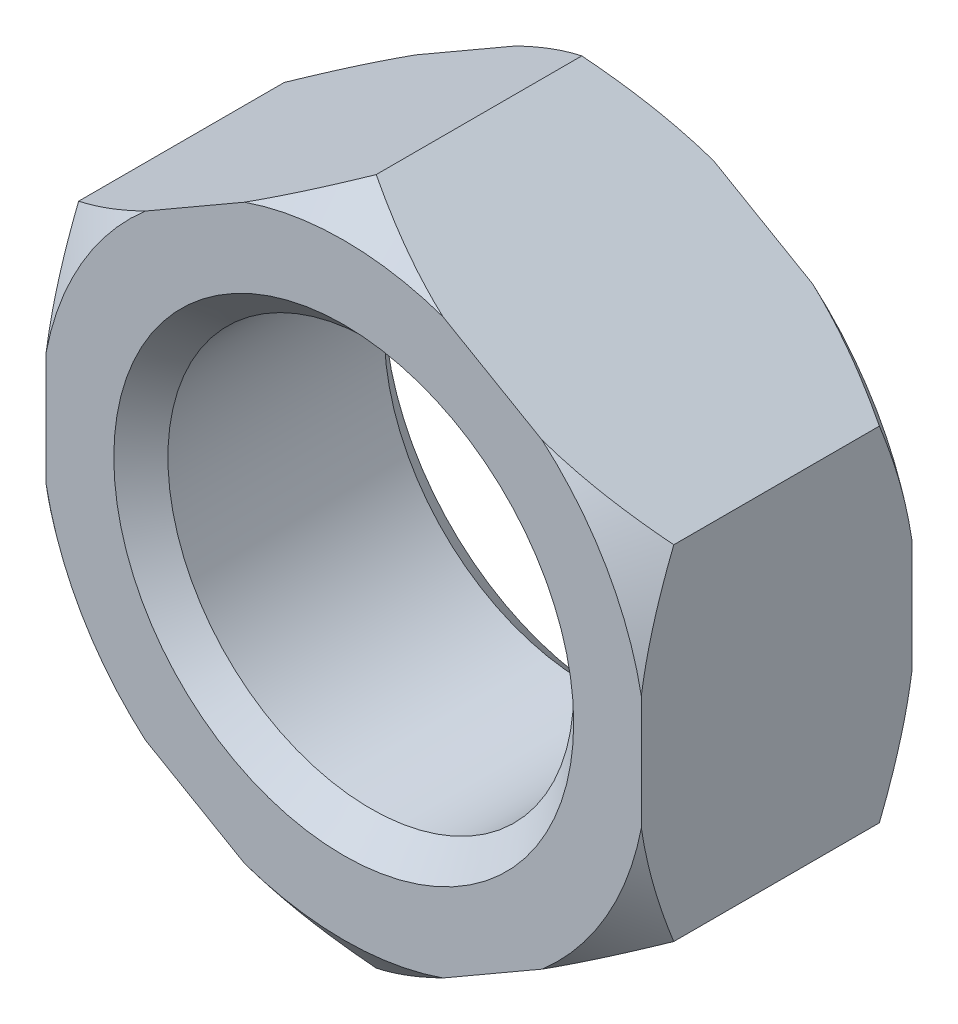
SolidWorks part; units mm, degrees
ref_plane "Front Plane" through (0, 0, 0) normal (0, 0, 1) x (1, 0, 0)
ref_plane "Top Plane" through (0, 0, 0) normal (0, 1, 0) x (1, 0, 0)
ref_plane "Right Plane" through (0, 0, 0) normal (1, 0, 0) x (0, 0, -1)
sketch "Sketch1" plane through (0, 0, 0) normal (0, 0, 1) x (1, 0, 0)
  line L1 (11, -6.3509) -> (11, 6.3509)
  line L2 (11, 6.3509) -> (0, 12.7017)
  line L3 (0, 12.7017) -> (-11, 6.3509)
  line L4 (-11, 6.3509) -> (-11, -6.3509)
  line L5 (-11, -6.3509) -> (0, -12.7017)
  line L6 (0, -12.7017) -> (11, -6.3509)
  circle A0 centre (0, 0) radius 11 construction
  dimension "D1" = 22
extrude "Boss-Extrude1" add sketch "Sketch1" along normal blind 10
sketch "Sketch2" plane through (0, 0, 10) normal (0, 0, 1) x (1, 0, 0)
  circle A0 centre (0, 0) radius 7.5
  dimension "D1" = 15
extrude "Cut-Extrude1" cut sketch "Sketch2" against normal through all
cosmetic thread "Cosmetic Thread2" parameters "D2"=18
chamfer "Chamfer1" distance 1 angle 45 2 edges at (7.5, 0, 10) (7.5, 0, 0)
sketch "Sketch3" plane through (0, 0, 0) normal (1, 0, 0) x (0, 0, -1)
  line L0 (-1.2, 12.7017) -> (0, 11.2017)
  line L1 (-10, 12.7017) -> (0, 12.7017) construction
  line L2 (0, 6.3509) -> (0, 12.7017) construction
  line L3 (0, 11.2017) -> (0, 12.7017)
  line L4 (0, 12.7017) -> (-1.2, 12.7017)
  line L5 (-10, 12.7017) -> (-8.8, 12.7017)
  line L6 (-8.8, 12.7017) -> (-10, 11.2017)
  line L7 (-10, 6.3509) -> (-10, 12.7017) construction
  line L8 (-10, 11.2017) -> (-10, 12.7017)
  line L9 (-11.931, 0) -> (4.498, 0) construction
  dimension "D1" = 1.5
  dimension "D2" = 1.2
  dimension "D3" = 1.5
  dimension "D4" = 1.2
revolve "Cut-Revolve1" cut sketch "Sketch3" angle 360 about L9
scale "Scale1" scale about centroid uniform scaling yes scale factor 0.25
